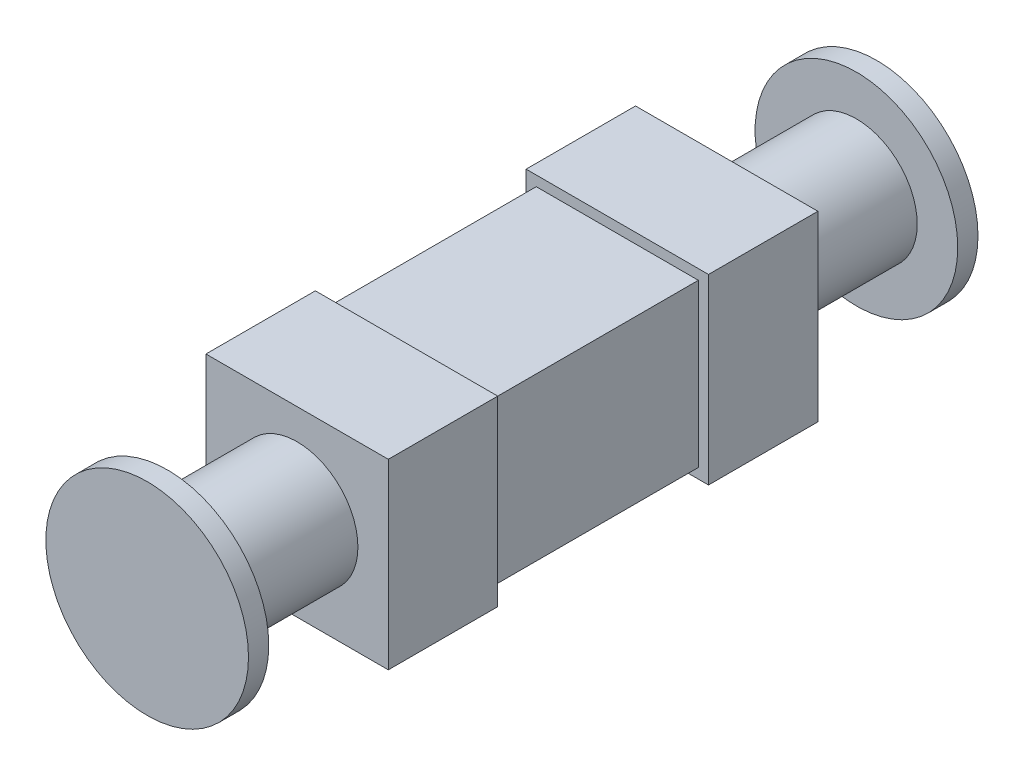
SolidWorks part; units mm, degrees
ref_plane "Front Plane" through (0, 0, 0) normal (0, 0, 1) x (1, 0, 0)
ref_plane "Top Plane" through (0, 0, 0) normal (0, 1, 0) x (1, 0, 0)
ref_plane "Right Plane" through (0, 0, 0) normal (1, 0, 0) x (0, 0, -1)
sketch "Sketch1" plane through (0, 0, 0) normal (1, 0, 0) x (0, 0, -1)
  line L0 (55, 0) -> (-55, 0) construction
  line L1 (-9, 0) -> (9, 0)
  line L2 (-9, 0) -> (-9, 2.5)
  line L4 (9, 0) -> (9, 2.5)
  line L5 (0, 0) -> (0, 1.5) construction
  line L6 (-5.3, 1.5) -> (-5.3, 2)
  line L7 (-5.3, 2) -> (5.3, 2)
  line L8 (5.3, 2) -> (5.3, 1.5)
  line L10 (-9, 2.5) -> (-8.5, 2.5)
  line L11 (-8.5, 2.5) -> (-8.5, 1.5)
  line L12 (-8.5, 1.5) -> (-5.3, 1.5)
  line L13 (5.3, 1.5) -> (8.5, 1.5)
  line L14 (8.5, 1.5) -> (8.5, 2.5)
  line L15 (8.5, 2.5) -> (9, 2.5)
  dimension "D1" = 18
  dimension "D2" = 2.5
  dimension "D3" = 3.7
  dimension "D4" = 2
  dimension "D5" = 2.5
  dimension "D6" = 0.5
  dimension "D7" = 1.5
  dimension "D8" = 0.5
revolve "Revolve1" add sketch "Sketch1" angle 360 about L1
sketch "Sketch2" plane through (0, 0, 5.3) normal (0, 0, 1) x (1, 0, 0)
  line L1 (2, -2) -> (-2, -2)
  line L2 (2, -2) -> (2, 2)
  line L3 (2, 2) -> (-2, 2)
  line L4 (-2, -2) -> (-2, 2)
  line L5 (2, -2) -> (-2, 2) construction
  line L6 (2, 2) -> (-2, -2) construction
  point P0 (0, 0)
  dimension "D1" = 4
extrude "Boss-Extrude1" add sketch "Sketch2" against normal up to surface (10.6 mm away) up to face at (2, 0, -5.3)
sketch "Sketch3" plane through (0, 0, 9) normal (0, 0, 1) x (1, 0, 0)
  circle A0 centre (0, 0) radius 0.8872
sketch "Sketch4" plane through (0, 0, 5.3) normal (0, 0, 1) x (1, 0, 0)
  line L1 (2.25, -2.25) -> (-2.25, -2.25)
  line L2 (2.25, -2.25) -> (2.25, 2.25)
  line L3 (2.25, 2.25) -> (-2.25, 2.25)
  line L4 (-2.25, -2.25) -> (-2.25, 2.25)
  line L5 (2.25, -2.25) -> (-2.25, 2.25) construction
  line L6 (2.25, 2.25) -> (-2.25, -2.25) construction
  point P0 (0, 0)
  dimension "D1" = 4.5
extrude "Boss-Extrude3" add sketch "Sketch4" against normal blind 2.7
mirror "Mirror1" about plane through (0, 0, 0) normal (0, 0, 1) of "Boss-Extrude3"
